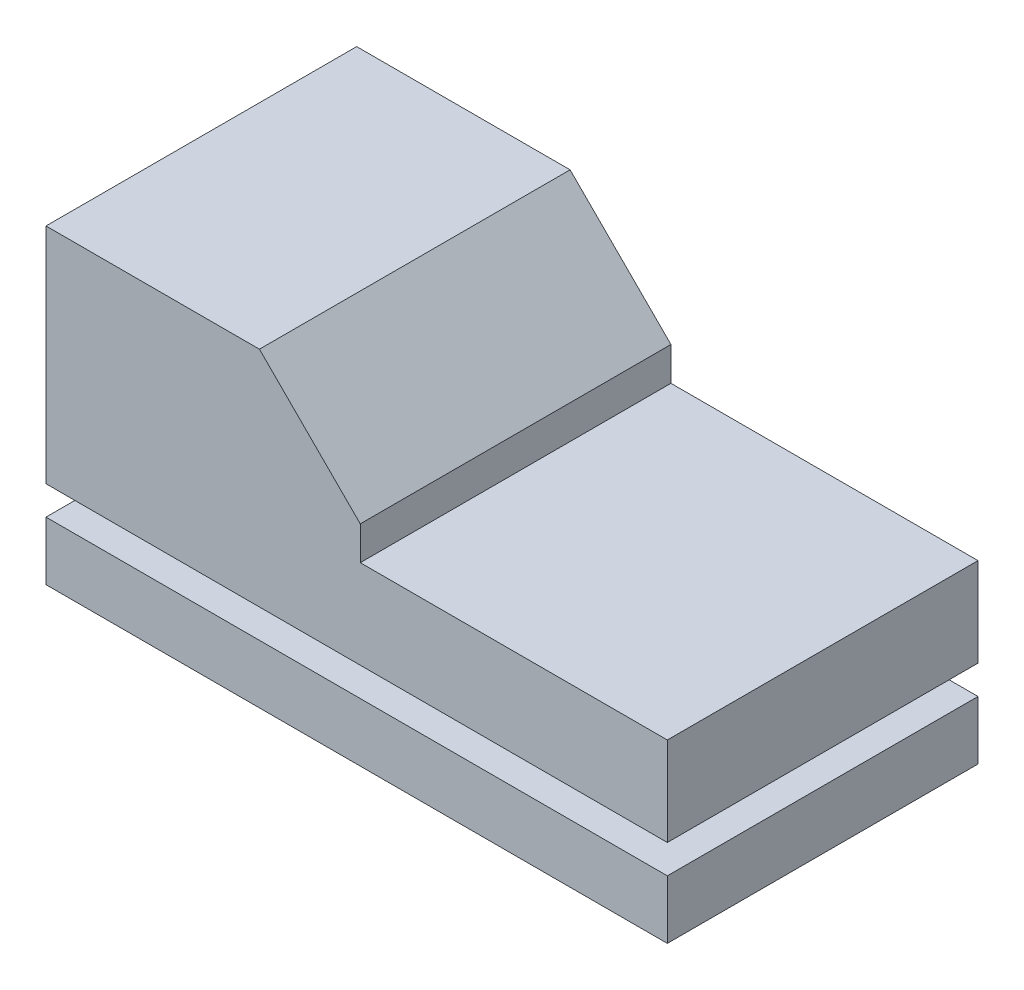
SolidWorks part; units mm, degrees
ref_plane "Front" through (0, 0, 0) normal (0, 0, 1) x (1, 0, 0)
ref_plane "Top" through (0, 0, 0) normal (0, 1, 0) x (1, 0, 0)
ref_plane "Right" through (0, 0, 0) normal (1, 0, 0) x (0, 0, -1)
sketch "Sketch1" plane through (0, 0, 0) normal (0, 0, 1) x (1, 0, 0)
  line L0 (0, 0) -> (0, 50.8)
  line L1 (0, 50.8) -> (34.9, 50.8)
  line L2 (34.9, 50.8) -> (51.39, 34.31)
  line L3 (51.39, 34.31) -> (51.39, 28.81)
  line L4 (51.39, 28.81) -> (101.6, 28.81)
  line L5 (101.6, 28.81) -> (101.6, 0)
  line L6 (101.6, 0) -> (0, 0)
  dimension "D1" = 101.6
  dimension "D2" = 50.8
  dimension "D3" = 34.9
  dimension "D4" = 5.5
  dimension "D5" = 28.81
  dimension "D6" = 135
extrude "Boss-Extrude1" add sketch "Sketch1" along normal mid plane 50.8
ref_plane "Plane1" through (0, 9.57, 0) normal (0, -1, 0) x (-1, 0, 0)
sketch "Sketch2" plane through (0, 9.57, 0) normal (0, -1, 0) x (-1, 0, 0)
  line L0 (-5.36, 20.04) -> (-96.24, 20.04)
  line L1 (0, 25.4) -> (-101.6, 25.4)
  line L2 (0, 25.4) -> (0, -25.4)
  line L3 (0, -25.4) -> (-101.6, -25.4)
  line L4 (-101.6, 25.4) -> (-101.6, -25.4)
  line L5 (-96.24, 20.04) -> (-96.24, -20.04)
  line L6 (-5.36, -20.04) -> (-96.24, -20.04)
  line L7 (-5.36, 20.04) -> (-5.36, -20.04)
  dimension "D1" = 5.36
extrude "Cut-Extrude1" cut sketch "Sketch2" against normal blind 4.72
sketch "Sketch3" plane through (0, 0, 0) normal (0, -1, 0) x (1, 0, 0)
  line L0 (101.6, 25.4) -> (101.6, -25.4) construction
  line L1 (9, 15) -> (91.6, 15)
  line L2 (9, 15) -> (9, -15)
  line L3 (9, -15) -> (91.6, -15)
  line L4 (91.6, 15) -> (91.6, -15)
  line L5 (0, 25.4) -> (0, -25.4) construction
  line L6 (0, -25.4) -> (101.6, -25.4) construction
  point P10 (9, 0)
  dimension "D1" = 10
  dimension "D2" = 9
  dimension "D3" = 10.4
extrude "Cut-Extrude2" cut sketch "Sketch3" against normal blind 8.43
